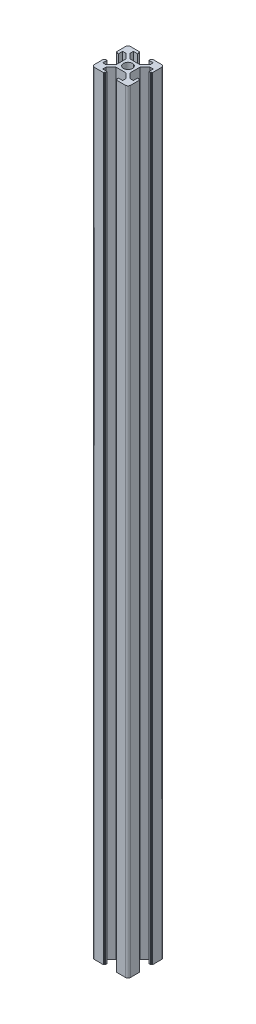
SolidWorks part; units mm, degrees
ref_plane "前视基准面" through (0, 0, 0) normal (0, 0, 1) x (1, 0, 0)
ref_plane "上视基准面" through (0, 0, 0) normal (0, 1, 0) x (1, 0, 0)
ref_plane "右视基准面" through (0, 0, 0) normal (1, 0, 0) x (0, 0, -1)
other "Configuration Table"
sketch "草图2" plane through (0, 0, 0) normal (0, 1, 0) x (1, 0, 0)
  line L0 (-3.6, 10) -> (-3.6, 9.5)
  line L1 (-3.6, 9.5) -> (-3.1, 9.5)
  line L2 (-3.1, 9.5) -> (-3.1, 8.5)
  line L3 (-3.1, 8.5) -> (-5.5, 8.5)
  line L4 (-8.5, -10) -> (-3.6, -10)
  line L5 (-10, -8.5) -> (-10, -3.6)
  line L6 (8.5, 10) -> (3.6, 10)
  line L7 (10, 8.5) -> (10, 3.6)
  line L8 (0, 14.8756) -> (0, 0) construction
  line L9 (0, 0) -> (14.1675, 0) construction
  line L10 (-5.5, 8.5) -> (-5.5, 6.65)
  line L11 (-5.5, 6.65) -> (-2.75, 3.9)
  line L12 (-2.75, 3.9) -> (2.75, 3.9)
  line L13 (5.5, 6.65) -> (2.75, 3.9)
  line L14 (5.5, 8.5) -> (5.5, 6.65)
  line L15 (3.1, 8.5) -> (5.5, 8.5)
  line L16 (3.1, 9.5) -> (3.1, 8.5)
  line L17 (3.6, 9.5) -> (3.1, 9.5)
  line L18 (3.6, 10) -> (3.6, 9.5)
  line L19 (-3.6, 10) -> (-8.5, 10)
  line L20 (10, 3.6) -> (9.5, 3.6)
  line L21 (9.5, 3.6) -> (9.5, 3.1)
  line L22 (9.5, 3.1) -> (8.5, 3.1)
  line L23 (8.5, 3.1) -> (8.5, 5.5)
  line L24 (8.5, 5.5) -> (6.65, 5.5)
  line L25 (6.65, 5.5) -> (3.9, 2.75)
  line L26 (3.9, 2.75) -> (3.9, -2.75)
  line L27 (6.65, -5.5) -> (3.9, -2.75)
  line L28 (8.5, -5.5) -> (6.65, -5.5)
  line L29 (8.5, -3.1) -> (8.5, -5.5)
  line L30 (9.5, -3.1) -> (8.5, -3.1)
  line L31 (9.5, -3.6) -> (9.5, -3.1)
  line L32 (10, -3.6) -> (9.5, -3.6)
  line L33 (3.6, -10) -> (3.6, -9.5)
  line L34 (3.6, -9.5) -> (3.1, -9.5)
  line L35 (3.1, -9.5) -> (3.1, -8.5)
  line L36 (3.1, -8.5) -> (5.5, -8.5)
  line L37 (5.5, -8.5) -> (5.5, -6.65)
  line L38 (5.5, -6.65) -> (2.75, -3.9)
  line L39 (2.75, -3.9) -> (-2.75, -3.9)
  line L40 (-5.5, -6.65) -> (-2.75, -3.9)
  line L41 (-5.5, -8.5) -> (-5.5, -6.65)
  line L42 (-3.1, -8.5) -> (-5.5, -8.5)
  line L43 (-3.1, -9.5) -> (-3.1, -8.5)
  line L44 (-3.6, -9.5) -> (-3.1, -9.5)
  line L45 (-3.6, -10) -> (-3.6, -9.5)
  line L46 (-10, -3.6) -> (-9.5, -3.6)
  line L47 (-9.5, -3.6) -> (-9.5, -3.1)
  line L48 (-9.5, -3.1) -> (-8.5, -3.1)
  line L49 (-8.5, -3.1) -> (-8.5, -5.5)
  line L50 (-8.5, -5.5) -> (-6.65, -5.5)
  line L51 (-6.65, -5.5) -> (-3.9, -2.75)
  line L52 (-3.9, -2.75) -> (-3.9, 2.75)
  line L53 (-6.65, 5.5) -> (-3.9, 2.75)
  line L54 (-8.5, 5.5) -> (-6.65, 5.5)
  line L55 (-8.5, 3.1) -> (-8.5, 5.5)
  line L56 (-9.5, 3.1) -> (-8.5, 3.1)
  line L57 (-9.5, 3.6) -> (-9.5, 3.1)
  line L58 (-10, 3.6) -> (-9.5, 3.6)
  line L59 (3.6, -10) -> (8.5, -10)
  line L60 (-10, 3.6) -> (-10, 8.5)
  line L61 (10, -3.6) -> (10, -8.5)
  circle A0 centre (0, 0) radius 2.5
  arc A1 (-10, 8.5) -> (-8.5, 10) centre (-8.5, 8.5) cw
  arc A2 (10, 8.5) -> (8.5, 10) centre (8.5, 8.5) ccw
  arc A3 (-8.5, -10) -> (-10, -8.5) centre (-8.5, -8.5) cw
  arc A4 (8.5, -10) -> (10, -8.5) centre (8.5, -8.5) ccw
  point P0 (-10, 0)
  point P1 (10, 0)
  point P2 (0, 10)
  point P3 (0, -10)
  point P4 (0, 0)
  point P5 (-10, -10)
  point P6 (10, -10)
  point P7 (10, 10)
  point P8 (-10, 10)
  point P36 (-10, 10)
  point P39 (10, 10)
  dimension "D1" = 11
  dimension "D2" = 20
  dimension "D3" = 6.2
  dimension "D4" = 7.2
  dimension "D5" = 6.1
  dimension "D6" = 5
  dimension "D7" = 1.5
  dimension "D8" = 45
  dimension "D9" = 0.5
  dimension "D10" = 1
  dimension "D11" = 5.5
extrude "凸台-拉伸1" add sketch "草图2" along normal blind 428
